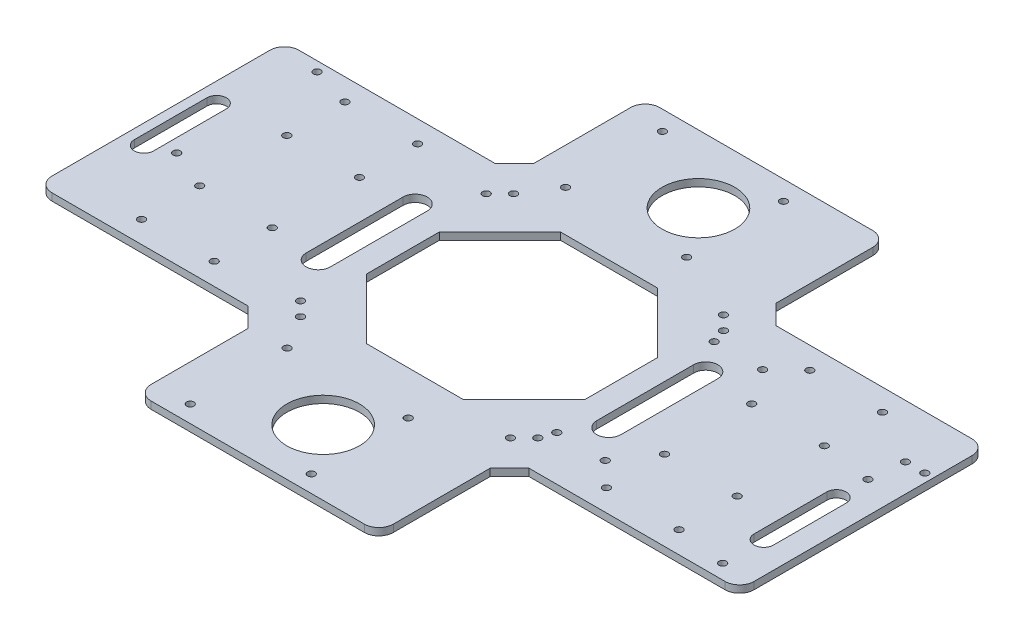
SolidWorks part; units mm, degrees
material "Thornel Mat VMA"
ref_plane "前视基准面" through (0, 0, 0) normal (0, 0, 1) x (1, 0, 0)
ref_plane "上视基准面" through (0, 0, 0) normal (0, 1, 0) x (1, 0, 0)
ref_plane "右视基准面" through (0, 0, 0) normal (1, 0, 0) x (0, 0, -1)
other "Configuration Table"
sketch "草图1" plane through (0, 0, 0) normal (0, 1, 0) x (1, 0, 0)
  line L0 (0, 0) -> (0, 105) construction
  line L1 (-145, -105) -> (145, -105)
  line L2 (-145, -105) -> (-145, 105)
  line L3 (-145, 105) -> (145, 105)
  line L4 (145, -105) -> (145, 105)
  line L5 (-145, -105) -> (145, 105) construction
  line L6 (-145, 105) -> (145, -105) construction
  line L7 (0, 0) -> (145, 0) construction
  line L8 (-50, 105) -> (-50, 51)
  line L9 (-50, 51) -> (-145, 51)
  line L10 (50, 51) -> (145, 51)
  line L11 (50, 105) -> (50, 51)
  line L12 (50, -51) -> (145, -51)
  line L13 (50, -105) -> (50, -51)
  line L14 (-50, -51) -> (-145, -51)
  line L15 (-50, -105) -> (-50, -51)
  point P0 (0, 0)
  dimension "D1" = 290
  dimension "D2" = 210
  dimension "D3" = 102
  dimension "D4" = 100
extrude "凸台-拉伸1" add sketch "草图1" along normal blind 3 contours L15 L1 L13 L12 L4 L10 L11 L3 L8 L9 L2 L14
sketch "草图2" plane through (0, 3, 0) normal (0, 1, 0) x (1, 0, 0)
  line L0 (0, 0) -> (145, 0) construction
  line L1 (145, -51) -> (145, 51) construction
  line L2 (0, 0) -> (0, 105) construction
  line L3 (-50, 105) -> (50, 105) construction
  line L4 (50, 51) -> (145, 51) construction
  circle A0 centre (111, 42) radius 1.5
  circle A1 centre (81, 42) radius 1.5
  circle A2 centre (81, 18) radius 1.5
  circle A3 centre (111, 18) radius 1.5
  circle A4 centre (111, -18) radius 1.5
  circle A5 centre (111, -42) radius 1.5
  circle A6 centre (81, -18) radius 1.5
  circle A7 centre (81, -42) radius 1.5
  circle A8 centre (-81, -42) radius 1.5
  circle A9 centre (-81, -18) radius 1.5
  circle A10 centre (-111, -42) radius 1.5
  circle A11 centre (-111, -18) radius 1.5
  circle A12 centre (-111, 18) radius 1.5
  circle A13 centre (-81, 18) radius 1.5
  circle A14 centre (-81, 42) radius 1.5
  circle A15 centre (-111, 42) radius 1.5
  dimension "D1" = 3
  dimension "D2" = 3
  dimension "D3" = 3
  dimension "D4" = 3
  dimension "D11" = 81
  dimension "D12" = 9
  dimension "D5" = 24
  dimension "D6" = 24
  dimension "D7" = 30
  dimension "D8" = 30
  dimension "D9" = 81
  dimension "D10" = 9
extrude "切除-拉伸1" cut sketch "草图2" against normal blind 3
sketch "草图3" plane through (0, 3, 0) normal (0, 1, 0) x (1, 0, 0)
  line L0 (-9.89, 0) -> (-9.89, 110.5115) construction
  line L1 (-9.89, 0) -> (145, 0) construction
  line L2 (145, -51) -> (145, 51) construction
  line L3 (-86.4083, 77) -> (66.6283, 77) construction
  line L4 (0, 0) -> (0, 108.4938) construction
  line L6 (-115.1345, -78) -> (96.1345, -78) construction
  line L7 (0, 0) -> (0, -114.288) construction
  line L8 (-9.89, 0) -> (-9.89, -143.8511) construction
  circle A5 centre (0, 77) radius 15
  circle A15 centre (0, -78) radius 15
  circle A28 centre (15.11, -58) radius 1.5
  circle A29 centre (15.11, -98) radius 1.5
  circle A30 centre (-34.89, -98) radius 1.5
  circle A31 centre (-34.89, -58) radius 1.5
  circle A33 centre (15.11, 97) radius 1.5
  circle A34 centre (15.11, 57) radius 1.5
  circle A35 centre (-34.89, 57) radius 1.5
  circle A36 centre (-34.89, 97) radius 1.5
  point P13 (-9.89, 77)
  dimension "D2" = 77
  dimension "D6" = 30
  dimension "D7" = 20
  dimension "D11" = 30
  dimension "D12" = 20
  dimension "D3" = 3
  dimension "D8" = 3
  dimension "D4" = 25
  dimension "D5" = 9.89
  dimension "D9" = 25
  dimension "D10" = 78
  dimension "D21" = 9.89
extrude "切除-拉伸2" cut sketch "草图3" against normal blind 10
sketch "草图4" plane through (0, 3, 0) normal (0, 1, 0) x (1, 0, 0)
  line L1 (-45, -40) -> (45, -40)
  line L2 (-45, -40) -> (-45, 40)
  line L3 (-45, 40) -> (45, 40)
  line L4 (45, -40) -> (45, 40)
  line L5 (-45, -40) -> (45, 40) construction
  line L6 (-45, 40) -> (45, -40) construction
  point P0 (0, 0)
  dimension "D1" = 90
  dimension "D2" = 80
extrude "切除-拉伸3" cut sketch "草图4" against normal blind 3
fillet "圆角3" radius 6 8 edges at (-50, 1.5, -105) (50, 1.5, -105) (145, 1.5, -51) (145, 1.5, 51) (-50, 1.5, 105) (50, 1.5, 105) (-145, 1.5, 51) (-145, 1.5, -51)
chamfer "倒角1" distance 8 angle 45 4 edges at (50, 1.5, 51) (-50, 1.5, 51) (50, 1.5, -51) (-50, 1.5, -51)
sketch "草图7" plane through (0, 3, 0) normal (0, 1, 0) x (1, 0, 0)
  line L0 (0, 0) -> (0, 142.9478) construction
  line L1 (0, 0) -> (-184.5222, 0) construction
  line L2 (-137, -15) -> (-137, 15) construction
  line L5 (-60, -20) -> (-60, 20) construction
  line L6 (-65, -20) -> (-65, 20)
  line L7 (-55, -20) -> (-55, 20)
  line L8 (0, 0) -> (165.4514, 0) construction
  line L14 (-110, 0) -> (-110, 75.2826) construction
  line L15 (132, -28) -> (132, 2) construction
  line L21 (60, -20) -> (60, 20) construction
  line L22 (65, -20) -> (65, 20)
  line L23 (55, -20) -> (55, 20)
  line L26 (132, -13) -> (163.2584, -13) construction
  line L27 (145, -45) -> (145, 45) construction
  line L30 (58, 51) -> (139, 51) construction
  line L33 (-141, -15) -> (-141, 15)
  line L34 (-133, -15) -> (-133, 15)
  line L35 (65, 0) -> (65, 55.2292) construction
  line L36 (0, -15) -> (172.3256, -15) construction
  line L37 (128, -28) -> (128, 2)
  line L38 (136, -28) -> (136, 2)
  arc A2 (-65, -20) -> (-55, -20) centre (-60, -20) ccw
  arc A3 (-55, 20) -> (-65, 20) centre (-60, 20) ccw
  arc A18 (65, -20) -> (55, -20) centre (60, -20) cw
  arc A19 (55, 20) -> (65, 20) centre (60, 20) cw
  circle A28 centre (141.5, 29) radius 1.5
  circle A29 centre (133.5, 29) radius 1.5
  arc A34 (-141, -15) -> (-133, -15) centre (-137, -15) ccw
  arc A35 (-133, 15) -> (-141, 15) centre (-137, 15) ccw
  arc A42 (128, -28) -> (136, -28) centre (132, -28) ccw
  arc A43 (136, 2) -> (128, 2) centre (132, 2) ccw
  circle A44 centre (132, 15) radius 1.5
  circle A45 centre (132, -45) radius 1.5
  circle A47 centre (51, 32.5) radius 1.5
  circle A49 centre (51, -32.5) radius 1.5
  circle A50 centre (71, 32.5) radius 1.5
  circle A51 centre (71, -32.5) radius 1.5
  point P6 (-137, 0)
  point P13 (-60, 0)
  point P21 (132, -13)
  point P27 (60, 0)
  dimension "D2" = 30
  dimension "D5" = 5
  dimension "D8" = 30
  dimension "D10" = 3
  dimension "D12" = 3
  dimension "D17" = 3.5
  dimension "D9" = 4
  dimension "D11" = 13
  dimension "D15" = 3
  dimension "D16" = 8
  dimension "D18" = 22
  dimension "D19" = 22
  dimension "D3" = 4
  dimension "D21" = 13
  dimension "D22" = 3
  dimension "D23" = 15
  dimension "D25" = 65
  dimension "D13" = 60
  dimension "D26" = 65
  dimension "D27" = 3
  dimension "D29" = 6
  dimension "D4" = 40
  dimension "D6" = 60
  dimension "D7" = 110
  dimension "D14" = 13
  dimension "D20" = 133
  dimension "D24" = 65
  dimension "D28" = 14
extrude "切除-拉伸6" cut sketch "草图7" against normal blind 10
chamfer "倒角2" distance 25 angle 45 4 edges at (45, 1.5, 40) (-45, 1.5, 40) (45, 1.5, -40) (-45, 1.5, -40)
sketch "草图8" plane through (0, 3, 0) normal (0, 1, 0) x (1, 0, 0)
  line L0 (0, 0) -> (0, 168.9929) construction
  line L1 (0, 0) -> (-169.1558, 0) construction
  line L2 (-103, 0) -> (-103, 65.828) construction
  line L3 (-103, 18) -> (-155.6162, 18) construction
  line L4 (0, 0) -> (-184.1789, 0) construction
  line L5 (0, 0) -> (0, 73.477) construction
  circle A12 centre (-127.5, 47) radius 1.5
  circle A14 centre (-127.5, -11) radius 1.5
  dimension "D1" = 3
  dimension "D2" = 24.5
  dimension "D3" = 58
  dimension "D4" = 103
  dimension "D5" = 18
  dimension "D6" = 0
extrude "切除-拉伸7" cut sketch "草图8" against normal blind 10
sketch "草图9" plane through (0, 3, 0) normal (0, 1, 0) x (1, 0, 0)
  line L0 (0, 0) -> (0, 165.3902) construction
  line L1 (0, 0) -> (179.4814, 0) construction
  line L2 (43.3431, 44) -> (49, 38.3431) construction
  line L3 (-55, -50) -> (55, -50) construction
  line L4 (-55, -50) -> (-55, 50) construction
  line L5 (-55, 50) -> (55, 50) construction
  line L6 (55, -50) -> (55, 50) construction
  line L7 (-55, -50) -> (55, 50) construction
  line L8 (-55, 50) -> (55, -50) construction
  circle A0 centre (43.3431, 44) radius 1.5
  circle A1 centre (49, 38.3431) radius 1.5
  circle A2 centre (49, -38.3431) radius 1.5
  circle A3 centre (43.3431, -44) radius 1.5
  circle A4 centre (-43.3431, -44) radius 1.5
  circle A5 centre (-49, -38.3431) radius 1.5
  circle A6 centre (-49, 38.3431) radius 1.5
  circle A7 centre (-43.3431, 44) radius 1.5
  dimension "D3" = 3
  dimension "D4" = 3
  dimension "D6" = 8
  dimension "D1" = 110
  dimension "D2" = 100
  dimension "D5" = 45
  dimension "D7" = 6
  dimension "D8" = 6
extrude "切除-拉伸8" cut sketch "草图9" against normal blind 10
